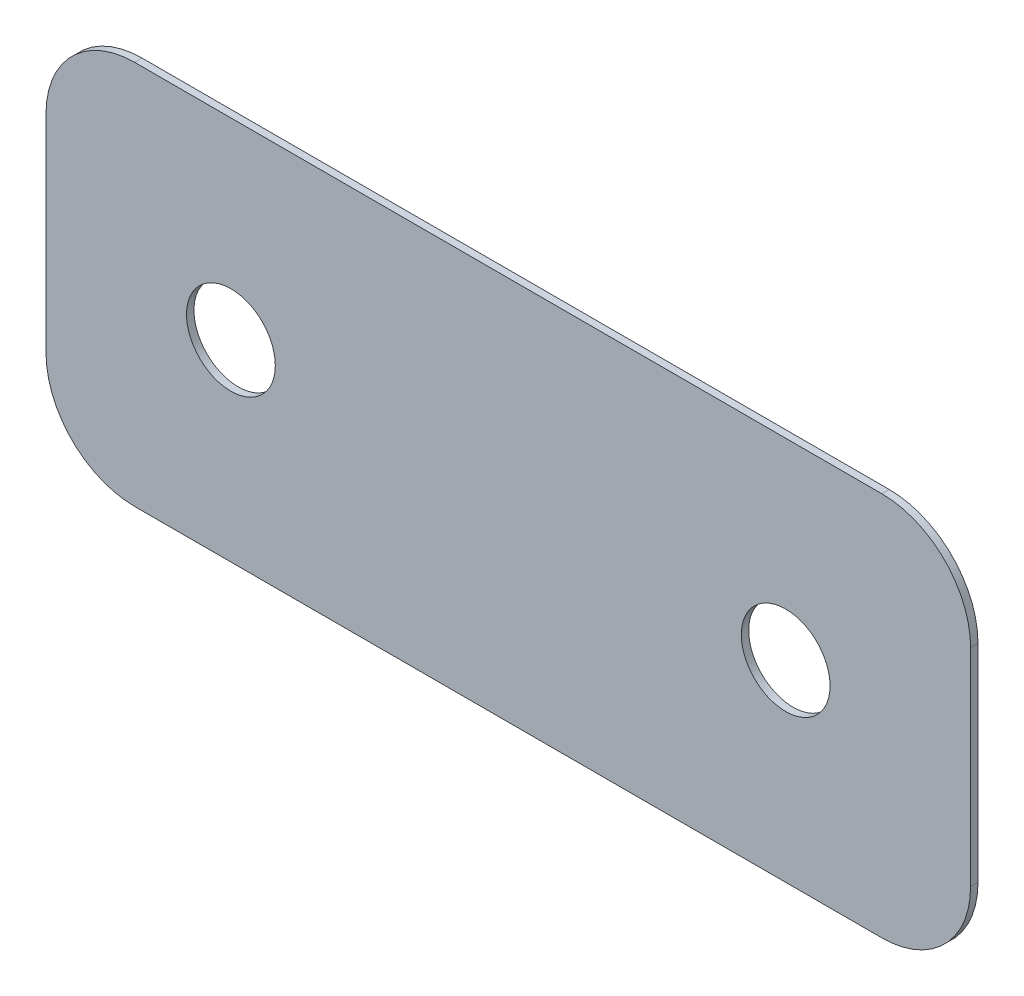
SolidWorks part; units mm, degrees
ref_plane "Front Plane" through (0, 0, 0) normal (0, 0, 1) x (1, 0, 0)
ref_plane "Top Plane" through (0, 0, 0) normal (0, 1, 0) x (1, 0, 0)
ref_plane "Right Plane" through (0, 0, 0) normal (1, 0, 0) x (0, 0, -1)
sketch "Sketch1" plane through (0, 0, 0) normal (0, 0, 1) x (1, 0, 0)
  line L1 (-50.5, 26) -> (50.5, 26)
  line L2 (-62.5, 14) -> (-62.5, -14)
  line L3 (-50.5, -26) -> (50.5, -26)
  line L4 (62.5, 14) -> (62.5, -14)
  line L5 (-62.5, 26) -> (62.5, -26) construction
  line L6 (-62.5, -26) -> (62.5, 26) construction
  circle A0 centre (-37.5, 0) radius 6
  circle A1 centre (37.5, 0) radius 6
  arc A2 (50.5, 26) -> (62.5, 14) centre (50.5, 14) cw
  arc A3 (50.5, -26) -> (62.5, -14) centre (50.5, -14) ccw
  arc A4 (-62.5, -14) -> (-50.5, -26) centre (-50.5, -14) ccw
  arc A5 (-50.5, 26) -> (-62.5, 14) centre (-50.5, 14) ccw
  point P0 (0, 0)
  dimension "D3" = 12
  dimension "D6" = 12
  dimension "D1" = 125
  dimension "D2" = 52
  dimension "D4" = 75
  dimension "D5" = 37.5
  dimension "D7" = 26
  dimension "D8" = 26
extrude "Boss-Extrude1" add sketch "Sketch1" along normal blind 1
